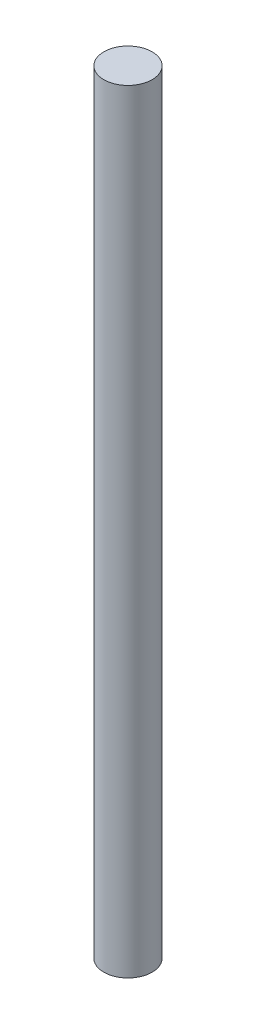
SolidWorks part; units mm, degrees
ref_plane "Front Plane" through (0, 0, 0) normal (0, 0, 1) x (1, 0, 0)
ref_plane "Top Plane" through (0, 0, 0) normal (0, 1, 0) x (1, 0, 0)
ref_plane "Right Plane" through (0, 0, 0) normal (1, 0, 0) x (0, 0, -1)
sketch "Sketch2" plane through (0, 0, 0) normal (0, 1, 0) x (1, 0, 0)
  circle A0 centre (0, 0) radius 2.5
  dimension "D1" = 5
extrude "Boss-Extrude1" add sketch "Sketch2" along normal blind 80
